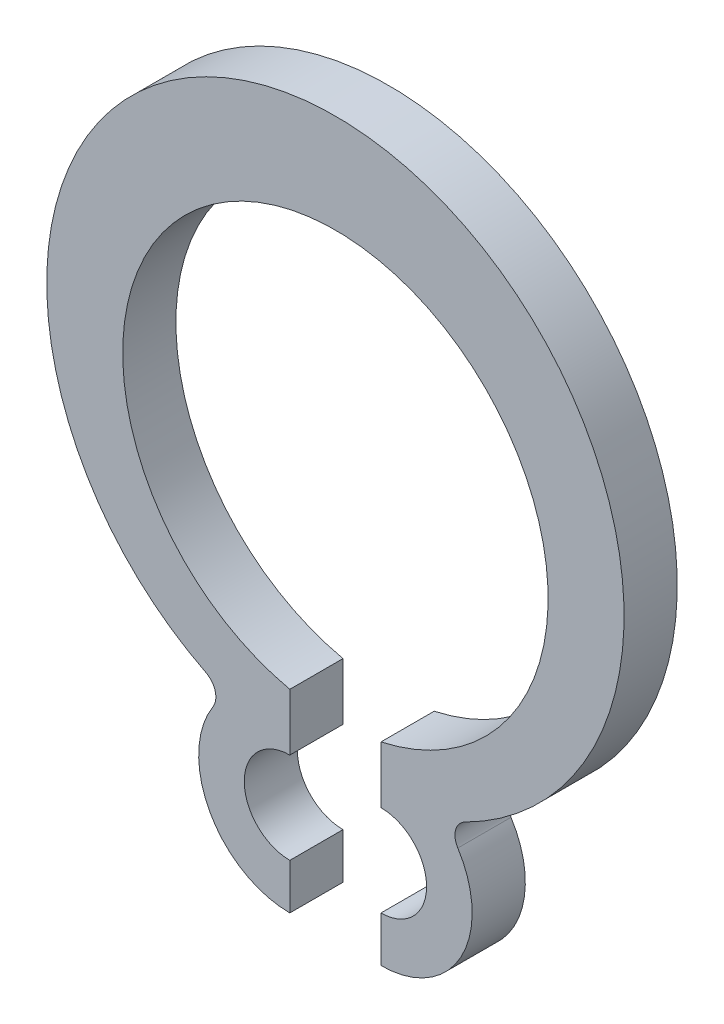
SolidWorks part; units mm, degrees
ref_plane "前视" through (0, 0, 0) normal (0, 0, 1) x (1, 0, 0)
ref_plane "上视" through (0, 0, 0) normal (0, 1, 0) x (1, 0, 0)
ref_plane "右视" through (0, 0, 0) normal (1, 0, 0) x (0, 0, -1)
sketch "尺寸草图" plane through (0, 0, 0) normal (0, 0, 1) x (1, 0, 0)
  line L0 (-1.8, 0) -> (-1.2, 0) construction
  line L1 (0, 0) -> (0, 0.7) construction
  line L2 (-1.2, 0) -> (-1.2, -5.1714) construction
  line L3 (1.2, 0) -> (1.2, -5.1714) construction
  line L4 (-0.6, 0) -> (-0.6, -5.6) construction
  line L5 (0.6, 0) -> (0.6, -5.1714) construction
  line L6 (-0.6, -2.735) -> (-0.6, -3.485)
  line L7 (-0.6, -4.685) -> (-0.6, -5.285)
  line L8 (0.6, -2.735) -> (0.6, -3.485)
  line L9 (0.6, -4.685) -> (0.6, -5.285)
  line L10 (0, 4.1) -> (0, 2.8) construction
  line L13 (-1.8, 0) -> (-1.8, -5.1714) construction
  line L14 (1.8, 0) -> (1.8, -5.1714) construction
  line L15 (-1.2, 0) -> (-0.6, 0) construction
  line L16 (-0.6, 0) -> (0, 0) construction
  line L17 (0, 0) -> (0.6, 0) construction
  line L18 (0.6, 0) -> (1.2, 0) construction
  line L19 (1.2, 0) -> (1.8, 0) construction
  arc A0 (0.6, -2.735) -> (-0.6, -2.735) centre (0, 0) ccw
  arc A1 (-1.6114, -3.4392) -> (-1.7059, -3.0955) centre (-1.8137, -3.31) ccw
  arc A2 (1.7059, -3.0955) -> (1.6114, -3.4392) centre (1.8137, -3.31) ccw
  arc A3 (0.6, -4.685) -> (0.6, -3.485) centre (0.6, -4.085) ccw
  arc A4 (-1.6114, -3.4392) -> (-0.6, -5.285) centre (-0.6, -4.085) ccw
  arc A6 (-0.6, -3.485) -> (-0.6, -4.685) centre (-0.6, -4.085) ccw
  arc A8 (0.6, -5.285) -> (1.6114, -3.4392) centre (0.6, -4.085) ccw
  arc A14 (1.7059, -3.0955) -> (-1.7059, -3.0955) centre (0, 0.3) ccw
  point P5 (0, -2.7)
  point P17 (-0.6, -2.735)
  point P25 (0.6, -2.735)
  dimension "D3" = 0.3
  dimension "0d1" = 1.2
  dimension "1d11" = 0.6
  dimension "d25" = 0.24
  dimension "d15" = 0.24
  dimension "d" = 2.8
  dimension "1d12" = 0.6
  dimension "d1" = 0.6
  dimension "h" = 1.35
  dimension "b" = 1.3
  dimension "dx" = 5.6
  dimension "S" = 0.7
  dimension "a" = 2.7
extrude "拉伸1" add sketch "尺寸草图" along normal blind 0.7
